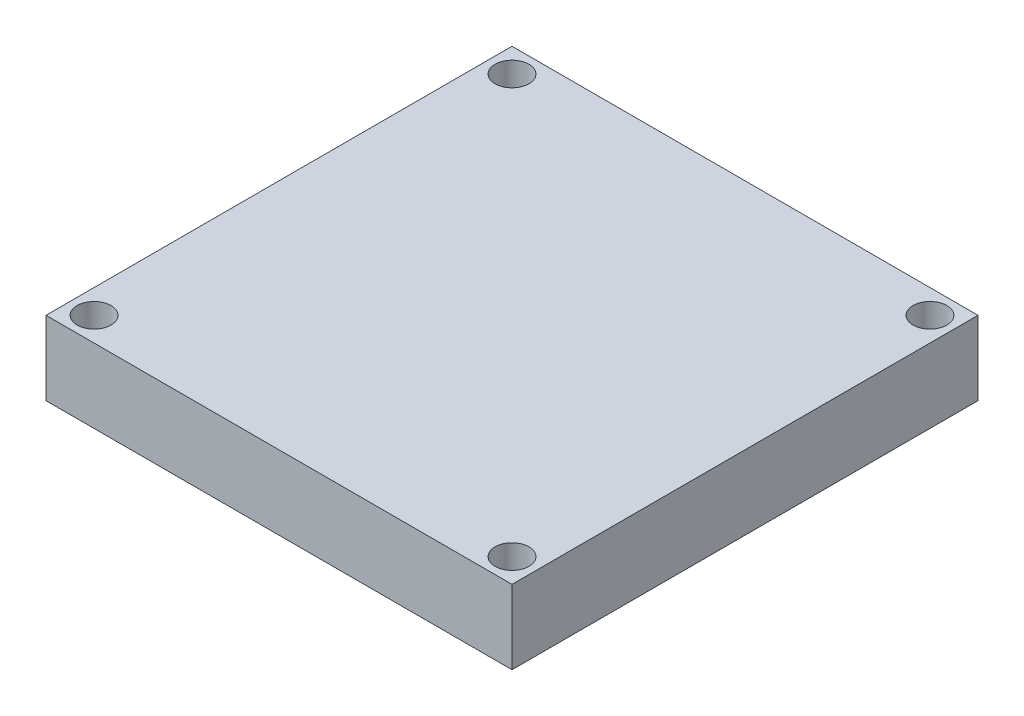
SolidWorks part; units mm, degrees
material "Alloy Steel"
ref_plane "Front Plane" through (0, 0, 0) normal (0, 0, 1) x (1, 0, 0)
ref_plane "Top Plane" through (0, 0, 0) normal (0, 1, 0) x (1, 0, 0)
ref_plane "Right Plane" through (0, 0, 0) normal (1, 0, 0) x (0, 0, -1)
sketch "Sketch1" plane through (0, 0, 0) normal (0, 1, 0) x (1, 0, 0)
  line L1 (-40.005, -40.005) -> (40.005, -40.005)
  line L2 (-40.005, -40.005) -> (-40.005, 40.005)
  line L3 (-40.005, 40.005) -> (40.005, 40.005)
  line L4 (40.005, -40.005) -> (40.005, 40.005)
  line L5 (-40.005, -40.005) -> (40.005, 40.005) construction
  line L6 (-40.005, 40.005) -> (40.005, -40.005) construction
  point P0 (0, 0)
  dimension "D1" = 80.01
  dimension "D2" = 80.01
extrude "Boss-Extrude1" add sketch "Sketch1" along normal blind 12.7
sketch "Sketch2" plane through (0, 12.7, 0) normal (0, 1, 0) x (1, 0, 0)
  line L0 (40.005, 40.005) -> (-40.005, 40.005) construction
  line L1 (-40.005, 40.005) -> (-40.005, -40.005) construction
  line L2 (0, 40.005) -> (0, 34.9084)
  line L3 (-40.005, 0) -> (-36.6073, 0)
  circle A0 centre (-35.8775, 35.8775) radius 2.9083
  circle A1 centre (35.8775, 35.8775) radius 2.9083
  circle A2 centre (35.8775, -35.8775) radius 2.9083
  circle A3 centre (-35.8775, -35.8775) radius 2.9083
  point P17 (0, 0)
  dimension "D1" = 4.1275
  dimension "D2" = 4.1275
extrude "Cut-Extrude1" cut sketch "Sketch2" against normal through all contours A0 | A1 | A3 | A2
